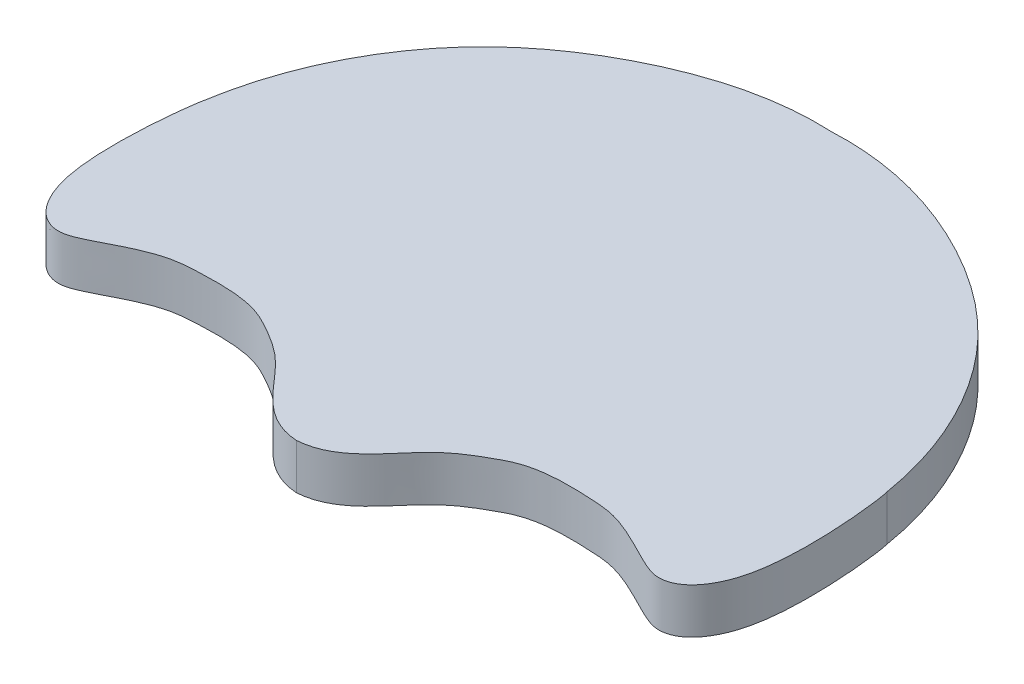
SolidWorks part; units mm, degrees
material "6061-T6 (SS)"
ref_plane "Front Plane" through (0, 0, 0) normal (0, 0, 1) x (1, 0, 0)
ref_plane "Top Plane" through (0, 0, 0) normal (0, 1, 0) x (1, 0, 0)
ref_plane "Right Plane" through (0, 0, 0) normal (1, 0, 0) x (0, 0, -1)
sketch "Sketch3" plane through (0, 0, 0) normal (0, 1, 0) x (1, 0, 0)
  line L0 (0, 0) -> (0, 159.1899) construction
  line L1 (0, 0) -> (0, -140.5301) construction
  line L2 (0, 0) -> (-190.5, 0) construction
  line L3 (0, 0) -> (190.5, 0) construction
  spline S0 degree 3 poles (-190.5, 0) (-184.3927, 37.537) (-157.2613, 93.9641) (-82.3875, 146.6227) (-31.3114, 160.7999) (0, 159.1899) knots 0 0 0 0 0.424401 0.65637 1 1 1 1
  spline S1 degree 3 poles (-190.5, 0) (-192.064, -4.9635) (-201.9672, -83.3146) (-174.6966, -109.29) (-151.6301, -100.568) (-131.4108, -87.7198) (-96.8436, -85.3754) (-78.6925, -86.2588) (-58.8335, -96.8794) (-37.3059, -109.9358) (-21.3496, -139.1148) (0, -140.5301) knots 0 0 0 0 0.166997 0.292321 0.319633 0.426735 0.458914 0.609242 0.64191 0.766802 1 1 1 1
  spline S2 degree 3 poles (190.5, 0) (192.064, -4.9635) (201.9672, -83.3146) (174.6966, -109.29) (151.6301, -100.568) (131.4108, -87.7198) (96.8436, -85.3754) (78.6925, -86.2588) (58.8335, -96.8794) (37.3059, -109.9358) (21.3496, -139.1148) (0, -140.5301) knots 0 0 0 0 0.166997 0.292321 0.319633 0.426735 0.458914 0.609242 0.64191 0.766802 1 1 1 1
  spline S3 degree 3 poles (190.5, 0) (184.3927, 37.537) (157.2613, 93.9641) (82.3875, 146.6227) (31.3114, 160.7999) (0, 159.1899) knots 0 0 0 0 0.424401 0.65637 1 1 1 1
  dimension "D1" = 381
  dimension "D2" = 299.72
  dimension "D3" = 159.1899
  dimension "D4" = 86.8953
  dimension "D5" = 104.4979
  dimension "D6" = 29.1616
  dimension "D7" = 92.2742
  dimension "D8" = 108.411
  dimension "D9" = 67.4883
  dimension "D10" = 43.7314
  dimension "D11" = 117.6915
  dimension "D12" = 162.2568
  dimension "D13" = 89.4522
  dimension "D14" = 140.1036
  dimension "D15" = 175.0666
  dimension "D16" = 50.2669
  dimension "D17" = 101.3666
  dimension "D18" = 138.1225
  dimension "D19" = 155.1557
  dimension "D20" = 192.0074
  dimension "D21" = 193.9268
  dimension "D23" = 76.6666
extrude "Boss-Extrude1" add sketch "Sketch3" along normal blind 25.4 from surface at 0 starting at plane "Top Plane"
sketch "Sketch5" plane through (0, 0, 0) normal (0, -1, 0) x (1, 0, 0)
  line L0 (0, 0) -> (0, -20.32) construction
  line L1 (31.75, -52.07) -> (-31.75, -52.07)
  line L2 (31.75, -52.07) -> (31.75, 11.43)
  line L3 (31.75, 11.43) -> (-31.75, 11.43)
  line L4 (-31.75, -52.07) -> (-31.75, 11.43)
  line L5 (31.75, -52.07) -> (-31.75, 11.43) construction
  line L6 (31.75, 11.43) -> (-31.75, -52.07) construction
  line L7 (-31.75, -52.07) -> (-31.75, -30.48)
  line L8 (-31.75, -30.48) -> (31.75, -30.48) construction
  line L9 (0, -20.32) -> (140.7253, -20.32) construction
  line L10 (0, -20.32) -> (0, -97.1287) construction
  line L11 (0, -20.32) -> (31.9753, -118.7297) construction
  line L13 (0, -20.32) -> (63.8443, -108.1942) construction
  line L14 (0, -20.32) -> (95.5392, -89.7333) construction
  line L15 (124.7166, -60.8429) -> (0, -20.32) construction
  line L16 (0, -20.32) -> (154.5508, 21.0918) construction
  line L17 (0, -20.32) -> (148.922, 65.6601) construction
  line L18 (0, -20.32) -> (-31.9753, -118.7297) construction
  line L19 (0, -20.32) -> (-63.8443, -108.1942) construction
  line L20 (0, -20.32) -> (-95.5392, -89.7333) construction
  line L21 (-124.7166, -60.8429) -> (0, -20.32) construction
  line L22 (0, -20.32) -> (-154.5508, 21.0918) construction
  line L23 (0, -20.32) -> (-148.922, 65.6601) construction
  spline S0 degree 3 poles (-148.922, 65.6601) (-157.8584, 40.2253) (-156.2837, 8.5854) (-143.1202, -28.9506) (-139.3242, -37.3463) (-130.3709, -53.1962) (-125.215, -60.649) (-118.0488, -69.1403) (-116.5795, -70.7975) (-113.5719, -74.0252) (-112.0368, -75.592) (-107.2801, -80.2116) (-103.9215, -83.1695) (-93.3361, -91.6595) (-85.5959, -96.8074) (-76.3408, -101.9556) (-75.3049, -102.5187) (-73.219, -103.6268) (-72.1677, -104.1726) (-69.0049, -105.7765) (-66.8862, -106.8006) (-60.5068, -109.7299) (-56.2231, -111.4921) (-47.6308, -114.6027) (-43.3223, -115.9511) (-34.7104, -118.209) (-30.4072, -119.1185) (-21.8242, -120.4791) (-17.5446, -120.9304) (-11.1443, -121.2499) (-9.0138, -121.2968) (-5.8216, -121.2757) (-4.1848, -121.2414) (-2.5489, -121.1705) (-1.9677, -121.1408) (-1.9605, -121.1404) (-1.2995, -121.1064) (-0.6497, -121.073) (0, -121.0396) knots -0.292878 -0.292878 -0.292878 -0.292878 0.125 0.125 0.25 0.25 0.375 0.375 0.40625 0.40625 0.4375 0.4375 0.5 0.5 0.625 0.625 0.640625 0.640625 0.65625 0.65625 0.6875 0.6875 0.75 0.75 0.8125 0.8125 0.875 0.875 0.9375 0.9375 0.96875 0.96875 0.984375 0.992798 0.992798 0.99292 0.99292 1 1 1 1
  spline S5 degree 3 poles (998.6789, -69.6893) (665.1581, -86.8384) (331.6156, -103.9885) (-1.9268, -121.1387) (-1.9605, -121.1404) (-1.9677, -121.1408) (-2.5489, -121.1705) (-4.1848, -121.2414) (-5.8216, -121.2757) (-9.0138, -121.2968) (-11.1443, -121.2499) (-17.5446, -120.9304) (-21.8242, -120.4791) (-30.4072, -119.1185) (-34.7104, -118.209) (-43.3223, -115.9511) (-47.6308, -114.6027) (-56.2231, -111.4921) (-60.5068, -109.7299) (-66.8862, -106.8006) (-69.0049, -105.7765) (-72.1677, -104.1726) (-73.219, -103.6268) (-75.3049, -102.5187) (-76.3408, -101.9556) (-85.5959, -96.8074) (-93.3361, -91.6595) (-103.9215, -83.1695) (-107.2801, -80.2116) (-112.0368, -75.592) (-113.5719, -74.0252) (-116.5795, -70.7975) (-118.0488, -69.1403) (-125.215, -60.649) (-130.3709, -53.1962) (-139.3242, -37.3463) (-143.1202, -28.9506) (-198.5095, 128.9933) (-22.362, 351.6373) (651.8169, -587.5188) knots -3.627409 -3.627409 -3.627409 -3.627409 0.006836 0.00708 0.00708 0.007202 0.007202 0.015625 0.03125 0.03125 0.0625 0.0625 0.125 0.125 0.1875 0.1875 0.25 0.25 0.3125 0.3125 0.34375 0.34375 0.359375 0.359375 0.375 0.375 0.5 0.5 0.5625 0.5625 0.59375 0.59375 0.625 0.625 0.75 0.75 0.875 0.875 3.034324 3.034324 3.034324 3.034324 only from (0, -121.0396) to (-152.8945, 6.1184)
  spline S6 degree 3 poles (-1687.8289, -2297.0686) (-150.4269, 537.0593) (218.9922, 187.4002) (143.1202, -28.9506) (139.3242, -37.3463) (130.3709, -53.1962) (125.215, -60.649) (118.0488, -69.1403) (116.5795, -70.7975) (113.5719, -74.0252) (112.0368, -75.592) (107.2801, -80.2116) (103.9215, -83.1695) (93.3361, -91.6595) (85.5959, -96.8074) (76.3408, -101.9556) (75.3049, -102.5187) (73.219, -103.6268) (72.1677, -104.1726) (69.0049, -105.7765) (66.8862, -106.8006) (60.5068, -109.7299) (56.2231, -111.4921) (47.6308, -114.6027) (43.3223, -115.9511) (34.7104, -118.209) (30.4072, -119.1185) (21.8242, -120.4791) (17.5446, -120.9304) (11.1443, -121.2499) (9.0138, -121.2968) (5.8216, -121.2757) (4.1848, -121.2414) (2.5489, -121.1705) (1.9677, -121.1408) (1.9605, -121.1404) (-997.3522, -69.7575) (-1996.6535, -18.3753) (-2996.029, 33.0152) knots -2.879056 -2.879056 -2.879056 -2.879056 0.125 0.125 0.25 0.25 0.375 0.375 0.40625 0.40625 0.4375 0.4375 0.5 0.5 0.625 0.625 0.640625 0.640625 0.65625 0.65625 0.6875 0.6875 0.75 0.75 0.8125 0.8125 0.875 0.875 0.9375 0.9375 0.96875 0.96875 0.984375 0.992798 0.992798 0.99292 0.99292 11.881939 11.881939 11.881939 11.881939 only from (152.8945, 6.1184) to (0, -121.0396)
  spline S8 degree 3 poles (148.922, 65.6601) (157.8584, 40.2253) (156.2837, 8.5854) (143.1202, -28.9506) (139.3242, -37.3463) (130.3709, -53.1962) (125.215, -60.649) (118.0488, -69.1403) (116.5795, -70.7975) (113.5719, -74.0252) (112.0368, -75.592) (107.2801, -80.2116) (103.9215, -83.1695) (93.3361, -91.6595) (85.5959, -96.8074) (76.3408, -101.9556) (75.3049, -102.5187) (73.219, -103.6268) (72.1677, -104.1726) (69.0049, -105.7765) (66.8862, -106.8006) (60.5068, -109.7299) (56.2231, -111.4921) (47.6308, -114.6027) (43.3223, -115.9511) (34.7104, -118.209) (30.4072, -119.1185) (21.8242, -120.4791) (17.5446, -120.9304) (11.1443, -121.2499) (9.0138, -121.2968) (5.8216, -121.2757) (4.1848, -121.2414) (2.5489, -121.1705) (1.9677, -121.1408) (1.9605, -121.1404) (1.2995, -121.1064) (0.6497, -121.073) (0, -121.0396) knots -0.292878 -0.292878 -0.292878 -0.292878 0.125 0.125 0.25 0.25 0.375 0.375 0.40625 0.40625 0.4375 0.4375 0.5 0.5 0.625 0.625 0.640625 0.640625 0.65625 0.65625 0.6875 0.6875 0.75 0.75 0.8125 0.8125 0.875 0.875 0.9375 0.9375 0.96875 0.96875 0.984375 0.992798 0.992798 0.99292 0.99292 1 1 1 1
  point P0 (0, -20.32)
  point P3 (0, -20.32)
  point P14 (0, 114.3)
  point P16 (0, 88.9)
  dimension "D1" = 20.32
  dimension "D2" = 63.5
  dimension "D3" = 63.5
  dimension "D4" = 21.59
  dimension "D6" = 25.4
  dimension "D7" = 88.9
  dimension "D8" = 18
  dimension "D9" = 18
  dimension "D10" = 18
  dimension "D11" = 18
  dimension "D12" = 15
  dimension "D13" = 15
  dimension "D5" = 38.1
equation "\"Plate thickness\"=1"
equation "\"D1@Boss-Extrude1\"=\"Plate thickness\""
equation "\"Bracket Alignment\"= .80"
equation "\"D1@Sketch5\"=\"Bracket Alignment\""
